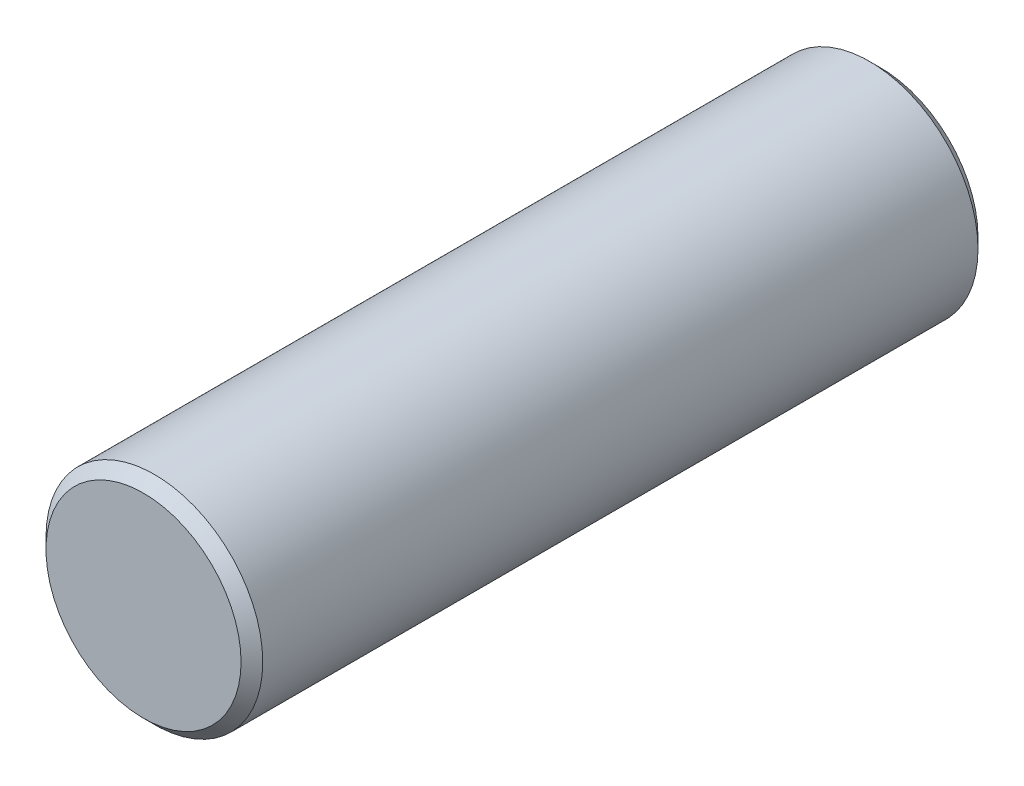
SolidWorks part; units mm, degrees
ref_plane "Front Plane" through (0, 0, 0) normal (0, 0, 1) x (1, 0, 0)
ref_plane "Top Plane" through (0, 0, 0) normal (0, 1, 0) x (1, 0, 0)
ref_plane "Right Plane" through (0, 0, 0) normal (1, 0, 0) x (0, 0, -1)
sketch "Sketch1" plane through (0, 0, 0) normal (0, 0, 1) x (1, 0, 0)
  circle A0 centre (0, 0) radius 5
  dimension "D1" = 10
extrude "Boss-Extrude1" add sketch "Sketch1" along normal mid plane 34
chamfer "Chamfer1" distance 0.5 angle 45 2 edges at (5, 0, -17) (5, 0, 17)
scale "Scale1" scale about origin uniform scaling yes scale factor 1.5
